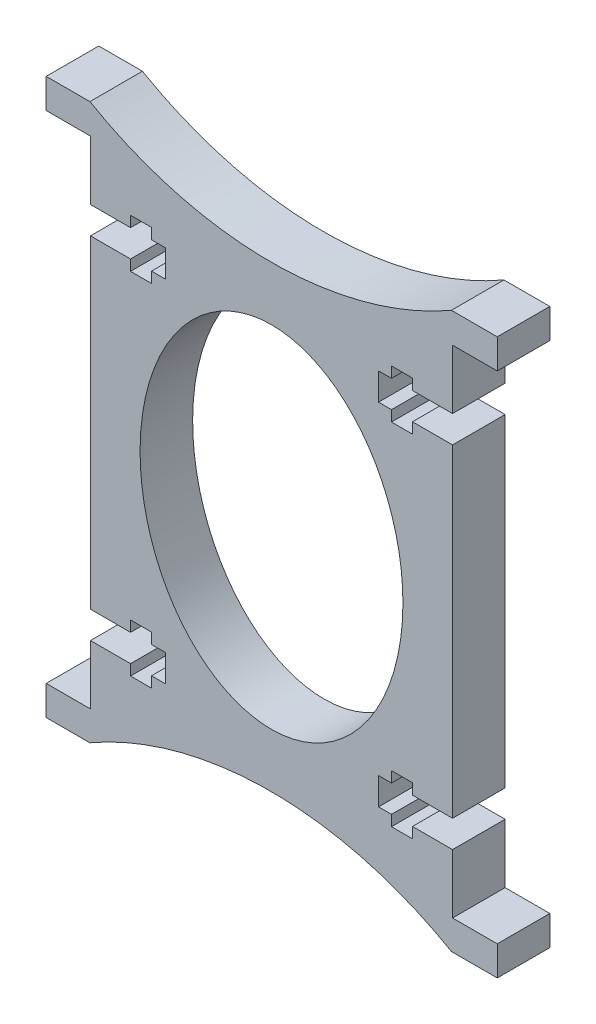
SolidWorks part; units mm, degrees
material "Acrylic (Medium-high impact)"
ref_plane "Front Plane" through (0, 0, 0) normal (0, 0, 1) x (1, 0, 0)
ref_plane "Top Plane" through (0, 0, 0) normal (0, 1, 0) x (1, 0, 0)
ref_plane "Right Plane" through (0, 0, 0) normal (1, 0, 0) x (0, 0, -1)
sketch "Sketch1" plane through (0, 0, 0) normal (0, 0, 1) x (1, 0, 0)
  line L0 (742.2468, 459.4261) -> (700.9179, 459.4261) construction
  line L1 (737.6724, 439.4261) -> (742.1973, 439.4261) construction
  line L2 (737.6724, 439.4261) -> (737.6724, 437.8782) construction
  line L3 (737.6724, 440.9739) -> (737.6724, 439.4261) construction
  line L4 (736.4752, 436.6538) -> (736.4752, 439.4261) construction
  line L5 (733.7999, 439.4261) -> (742.1973, 439.4261) construction
  line L6 (736.4752, 442.1983) -> (736.4752, 439.4261) construction
  line L7 (735.2781, 436.6538) -> (737.6724, 436.6538)
  line L8 (700.9179, 459.4261) -> (700.9179, 440.9739)
  line L9 (706.6895, 442.1983) -> (706.6895, 439.4261) construction
  line L10 (735.2781, 442.1983) -> (737.6724, 442.1983)
  line L11 (733.7999, 440.9739) -> (733.7999, 437.8782)
  line L12 (742.2468, 437.8782) -> (742.2468, 431.1161)
  line L13 (742.2468, 437.8782) -> (737.6724, 437.8782)
  line L14 (737.6724, 440.9739) -> (742.2468, 440.9739)
  line L15 (747.3486, 427.7361) -> (747.3486, 431.1161)
  line L16 (742.1149, 427.7361) -> (747.3486, 427.7361)
  line L17 (709.4867, 439.4261) -> (700.9179, 439.4261) construction
  line L18 (707.8867, 436.6538) -> (707.8867, 437.8782)
  line L19 (707.8867, 440.9739) -> (709.4867, 440.9739)
  line L20 (707.8867, 437.8782) -> (709.4867, 437.8782)
  line L21 (707.8867, 440.9739) -> (707.8867, 442.1983)
  line L22 (706.6895, 436.6538) -> (706.6895, 439.4261) construction
  line L23 (705.4923, 436.6538) -> (705.4923, 437.8782)
  line L24 (705.4923, 440.9739) -> (705.4923, 442.1983)
  line L25 (705.4923, 440.9739) -> (705.4923, 439.4261) construction
  line L26 (705.4923, 439.4261) -> (705.4923, 437.8782) construction
  line L27 (695.8656, 431.1161) -> (700.9179, 431.1161)
  line L28 (700.8541, 427.7361) -> (695.8656, 427.7361)
  line L29 (695.8656, 427.7361) -> (695.8656, 431.1161)
  line L30 (705.4923, 440.9739) -> (700.9179, 440.9739)
  line L31 (700.9179, 437.8782) -> (705.4923, 437.8782)
  line L32 (700.9179, 437.8782) -> (700.9179, 431.1161)
  line L33 (705.4923, 439.4261) -> (700.9179, 439.4261) construction
  line L34 (709.4867, 440.9739) -> (709.4867, 437.8782)
  line L35 (747.3486, 431.1161) -> (742.2468, 431.1161)
  line L36 (737.6724, 440.9739) -> (737.6724, 442.1983)
  line L37 (737.6724, 436.6538) -> (737.6724, 437.8782)
  line L38 (735.2781, 440.9739) -> (735.2781, 442.1983)
  line L39 (735.2781, 437.8782) -> (733.7999, 437.8782)
  line L40 (735.2781, 440.9739) -> (733.7999, 440.9739)
  line L41 (735.2781, 436.6538) -> (735.2781, 437.8782)
  line L42 (742.2468, 459.4261) -> (742.2468, 440.9739)
  line L43 (705.4923, 479.4261) -> (700.9179, 479.4261) construction
  line L44 (707.8867, 442.1983) -> (705.4923, 442.1983)
  line L45 (705.4923, 479.4261) -> (705.4923, 480.9739) construction
  line L46 (705.4923, 477.8782) -> (705.4923, 479.4261) construction
  line L47 (706.6895, 482.1983) -> (706.6895, 479.4261) construction
  line L48 (709.4867, 479.4261) -> (700.9179, 479.4261) construction
  line L49 (706.6895, 476.6538) -> (706.6895, 479.4261) construction
  line L50 (736.4752, 476.6538) -> (736.4752, 479.4261) construction
  line L51 (733.7999, 479.4261) -> (742.1973, 479.4261) construction
  line L52 (736.4752, 482.1983) -> (736.4752, 479.4261) construction
  line L53 (737.6724, 477.8782) -> (737.6724, 479.4261) construction
  line L54 (737.6724, 479.4261) -> (737.6724, 480.9739) construction
  line L55 (737.6724, 479.4261) -> (742.1973, 479.4261) construction
  line L56 (707.8867, 482.1983) -> (705.4923, 482.1983)
  line L57 (707.8867, 476.6538) -> (705.4923, 476.6538)
  line L58 (742.2468, 459.4261) -> (742.2468, 477.8782)
  line L59 (735.2781, 482.1983) -> (735.2781, 480.9739)
  line L61 (707.8867, 436.6538) -> (705.4923, 436.6538)
  line L62 (735.2781, 477.8782) -> (733.7999, 477.8782)
  line L63 (735.2781, 480.9739) -> (733.7999, 480.9739)
  line L64 (735.2781, 477.8782) -> (735.2781, 476.6538)
  line L65 (737.6724, 482.1983) -> (737.6724, 480.9739)
  line L66 (737.6724, 477.8782) -> (737.6724, 476.6538)
  line L67 (747.3486, 487.7361) -> (742.2468, 487.7361)
  line L68 (709.4867, 477.8782) -> (709.4867, 480.9739)
  line L69 (700.9179, 480.9739) -> (700.9179, 487.7361)
  line L70 (700.9179, 480.9739) -> (705.4923, 480.9739)
  line L71 (705.4923, 477.8782) -> (700.9179, 477.8782)
  line L72 (695.8656, 491.1161) -> (695.8656, 487.7361)
  line L73 (700.8541, 491.1161) -> (695.8656, 491.1161)
  line L74 (695.8656, 487.7361) -> (700.9179, 487.7361)
  line L75 (705.4923, 477.8782) -> (705.4923, 476.6538)
  line L76 (705.4923, 482.1983) -> (705.4923, 480.9739)
  line L77 (707.8867, 477.8782) -> (707.8867, 476.6538)
  line L78 (707.8867, 480.9739) -> (709.4867, 480.9739)
  line L79 (707.8867, 477.8782) -> (709.4867, 477.8782)
  line L80 (707.8867, 482.1983) -> (707.8867, 480.9739)
  line L81 (742.1149, 491.1161) -> (747.3486, 491.1161)
  line L82 (747.3486, 491.1161) -> (747.3486, 487.7361)
  line L83 (737.6724, 477.8782) -> (742.2468, 477.8782)
  line L84 (742.2468, 480.9739) -> (737.6724, 480.9739)
  line L85 (742.2468, 480.9739) -> (742.2468, 487.7361)
  line L86 (733.7999, 477.8782) -> (733.7999, 480.9739)
  line L87 (735.2781, 476.6538) -> (737.6724, 476.6538)
  line L88 (700.9179, 459.4261) -> (700.9179, 477.8782)
  line L89 (735.2781, 482.1983) -> (737.6724, 482.1983)
  line L90 (721.5824, 459.4261) -> (706.5824, 459.4261) construction
  line L91 (700.9179, 480.9739) -> (700.9179, 477.8782) construction
  line L92 (700.9179, 487.7361) -> (700.8541, 491.1161) construction
  line L93 (700.9179, 431.1161) -> (700.8541, 427.7361) construction
  arc A0 (700.8541, 491.1161) -> (742.1149, 491.1161) centre (721.4845, 526.8562) ccw
  arc A1 (700.8541, 427.7361) -> (742.1149, 427.7361) centre (721.4845, 391.996) cw
  ellipse E0 centre (721.5824, 459.4261) end of major axis (721.5824, 479.4261) minor radius 15
  point P38 (721.5824, 459.4261)
  point P102 (700.886, 489.4261)
  point P103 (700.886, 429.4261)
  dimension "D1" = 60
  dimension "D2" = 3.0957
  dimension "D3" = 3.38
  dimension "D4" = 10
  dimension "D5" = 1.6
extrude "Boss-Extrude1" add sketch "Sketch1" along normal blind 6
